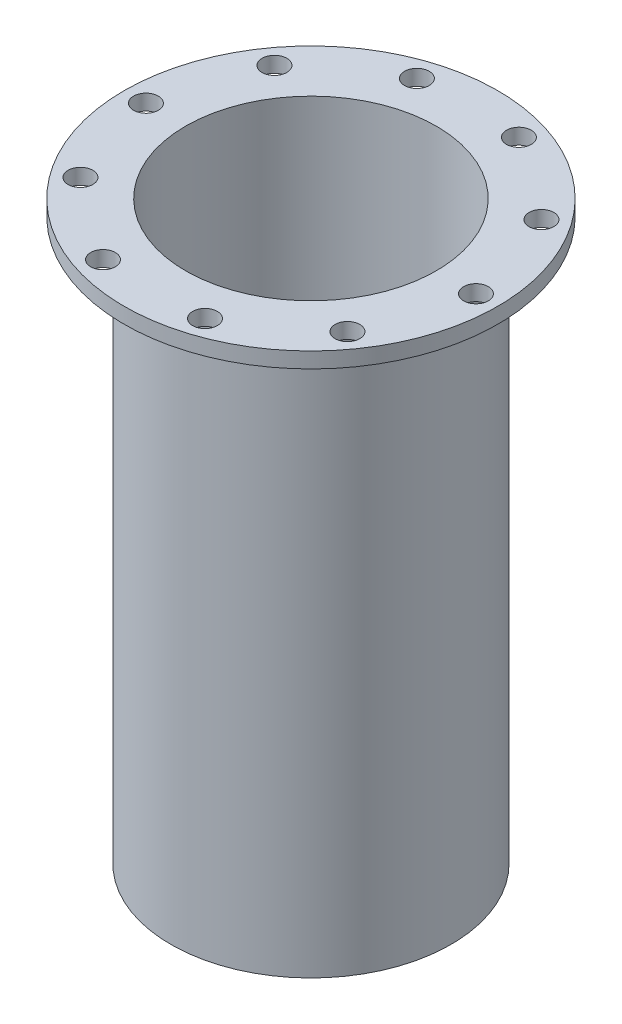
SolidWorks part; units mm, degrees
ref_plane "Front Plane" through (0, 0, 0) normal (0, 0, 1) x (1, 0, 0)
ref_plane "Top Plane" through (0, 0, 0) normal (0, 1, 0) x (1, 0, 0)
ref_plane "Right Plane" through (0, 0, 0) normal (1, 0, 0) x (0, 0, -1)
sketch "Sketch1" plane through (0, 0, 0) normal (0, 0, 1) x (1, 0, 0)
  line L0 (0, 0) -> (0, -134.8652) construction
  line L1 (51.1302, 0) -> (51.1302, -220.345)
  line L2 (51.1302, -234.95) -> (57.15, -234.95)
  line L3 (57.15, -234.95) -> (57.15, -6.35)
  line L4 (57.15, -6.35) -> (76.2, -6.35)
  line L5 (76.2, -6.35) -> (76.2, 0)
  line L6 (76.2, 0) -> (51.1302, 0)
  line L7 (51.1302, -220.345) -> (53.6702, -220.345)
  line L8 (53.6702, -220.345) -> (53.6702, -223.393)
  line L9 (53.6702, -223.393) -> (51.1302, -223.393)
  line L10 (-50.927, -217.17) -> (50.927, -217.17) construction
  line L11 (51.1302, -223.393) -> (51.1302, -234.95)
  dimension "D1" = 51.1302
  dimension "D2" = 57.15
  dimension "D3" = 76.2
  dimension "D4" = 6.35
  dimension "D5" = 234.95
  dimension "D6" = 3.175
  dimension "D7" = 3.048
  dimension "D8" = 2.54
revolve "Revolve1" add sketch "Sketch1" angle 360 about L0
hole_wizard "Tap Drill for 3/8-16 Tap1" positions "Sketch2" profile "Sketch3" hole size "3/8" standard "ANSI Inch" end condition through all
sketch "Sketch2" plane through (0, 0, 0) normal (0, 1, 0) x (1, 0, 0)
  point P1 (67.31, 0)
  dimension "D1" = 67.31
sketch "Sketch3" plane through (67.31, 0, 0) normal (1, 0, 0) x (0, 0, 1)
  line L0 (0, 0) -> (0, 234.95)
  line L1 (0, 234.95) -> (5.0419, 234.95)
  line L2 (5.0419, 234.95) -> (5.0419, 0)
  line L5 (5.0419, 0) -> (0, 0)
  line L11 (0, -6.35) -> (0, 107.95) construction
  dimension "Thru Hole Dia." = 10.0838
  dimension "Thru Hole Depth" = 234.95
pattern_circular "CirPattern1" count 10 over 360 about axis through (0, 0, 0) along (0, 1, 0) of "Tap Drill for 3/8-16 Tap1"
